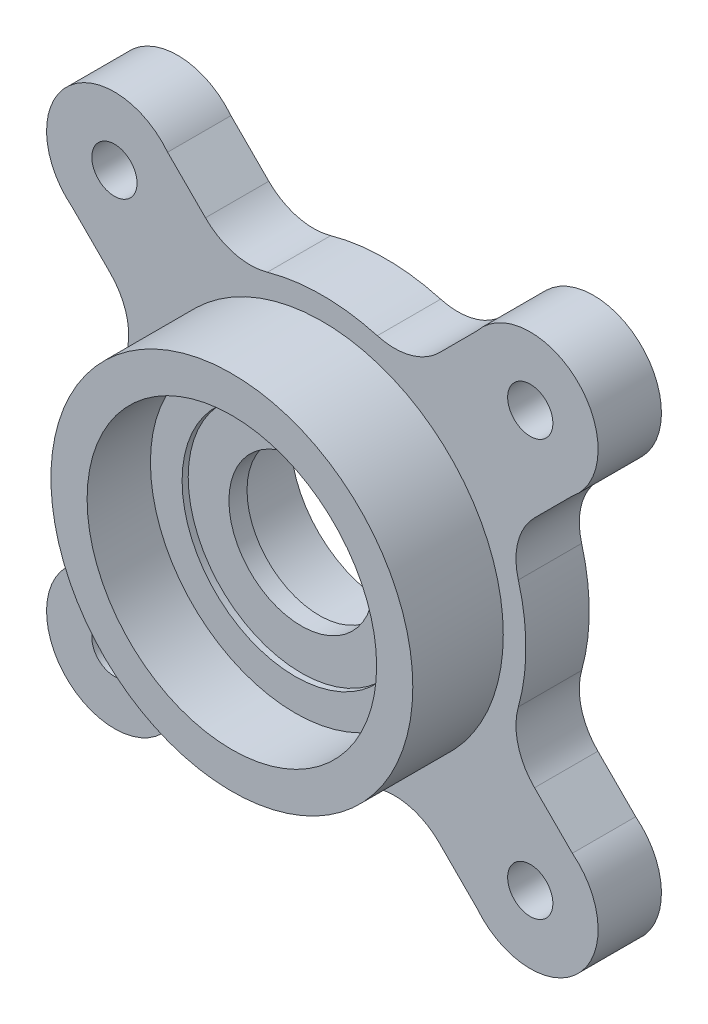
SolidWorks part; units mm, degrees
material "6061 Alloy"
ref_plane "Front Plane" through (0, 0, 0) normal (0, 0, 1) x (1, 0, 0)
ref_plane "Top Plane" through (0, 0, 0) normal (0, 1, 0) x (1, 0, 0)
ref_plane "Right Plane" through (0, 0, 0) normal (1, 0, 0) x (0, 0, -1)
sketch "Sketch1" plane through (0, 0, 0) normal (0, 0, 1) x (1, 0, 0)
  line L0 (17.1012, -27.6369) -> (-27.6369, 17.1012)
  line L1 (-22.981, -22.981) -> (22.981, -22.981) construction
  line L2 (-22.981, -22.981) -> (-22.981, 22.981) construction
  line L3 (-22.981, 22.981) -> (22.981, 22.981) construction
  line L4 (22.981, -22.981) -> (22.981, 22.981) construction
  line L5 (-22.981, -22.981) -> (22.981, 22.981) construction
  line L6 (-22.981, 22.981) -> (22.981, -22.981) construction
  line L7 (17.1012, -27.6369) -> (27.6369, -17.1012)
  line L8 (-27.6369, 17.1012) -> (-17.1012, 27.6369)
  line L9 (27.6369, -17.1012) -> (-17.1012, 27.6369)
  line L10 (17.1012, -27.6369) -> (-17.1012, 27.6369) construction
  line L11 (-27.6369, 17.1012) -> (27.6369, -17.1012) construction
  line L12 (-27.6369, -17.1012) -> (17.1012, 27.6369)
  line L13 (-27.6369, -17.1012) -> (-17.1012, -27.6369)
  line L14 (17.1012, 27.6369) -> (27.6369, 17.1012)
  line L15 (-17.1012, -27.6369) -> (27.6369, 17.1012)
  line L16 (-27.6369, -17.1012) -> (27.6369, 17.1012) construction
  line L17 (17.1012, 27.6369) -> (-17.1012, -27.6369) construction
  circle A0 centre (0, 0) radius 22.5
  circle A1 centre (0, 0) radius 32.5 construction
  circle A2 centre (-22.981, 22.981) radius 7.5
  circle A3 centre (-22.981, -22.981) radius 7.5
  circle A4 centre (22.981, -22.981) radius 7.5
  circle A5 centre (22.981, 22.981) radius 7.5
  point P12 (-22.3691, 22.3691)
  point P13 (22.3691, 22.3691)
  dimension "D1" = 45
  dimension "D2" = 65
  dimension "D3" = 15
extrude ".5 in sheet" add sketch "Sketch1" along normal blind 7 contours A5 A0 A2 A3 A4 | A0 A2 | A0 A5 | A0 A4 | A0 A3 | L8 A2 | A2 L0 A0 L9 | L9 A0 L0 L12 | L12 A0 L9 | L0 A0 L12 | L15 A0 L0 | L0 A0 L9 L15 | L9 A0 L15 | L15 A0 L12 L9 | L0 L15 L9 L12 | L14 A5 | A5 L12 A0 L15 | L7 A4 | A4 L9 A0 L0 | L13 A3 | A3 L15 A0 L12
fillet "Fillet1" radius 7 8 edges at (-9.7446, -20.2804, 3.5) (20.2804, 9.7446, 3.5) (-9.7446, 20.2804, 3.5) (20.2804, -9.7446, 3.5) (-20.2804, 9.7446, 3.5) (9.7446, -20.2804, 3.5) (-20.2804, -9.7446, 3.5) (9.7446, 20.2804, 3.5)
hole_wizard "Ø5.0 Reamed over for shoulder bolt" positions "Sketch6" profile "Sketch5" hole size "Ø5.0" standard "ANSI Metric" end condition through all
sketch "Sketch6" plane through (-11.0554, 12.7771, 7) normal (0, 0, 1) x (1, 0, 0)
  point P0 (-11.9256, 10.2039)
  point P3 (34.0364, 10.2039)
  point P6 (34.0364, -35.7581)
  point P9 (-11.9256, -35.7581)
sketch "Sketch5" plane through (-22.981, 22.981, 7) normal (1, 0, 0) x (0, -1, 0)
  line L0 (0, 0) -> (0, 7)
  line L1 (0, 7) -> (2.5, 7)
  line L2 (2.5, 7) -> (2.5, 0)
  line L5 (2.5, 0) -> (0, 0)
  line L11 (0, -6.35) -> (0, 107.95) construction
  dimension "Thru Hole Dia." = 5
  dimension "Thru Hole Depth" = 7
sketch "Sketch8" plane through (0, 0, 7) normal (0, 0, 1) x (1, 0, 0)
  circle A0 centre (0, 0) radius 20
  dimension "D1" = 40
extrude "Boss-Extrude2" add sketch "Sketch8" along normal blind 10
sketch "Sketch2" plane through (0, 0, 0) normal (0, 0, 1) x (1, 0, 0)
  circle A0 centre (0, 0) radius 8
  dimension "D1" = 16
extrude "Through hole" cut sketch "Sketch2" along normal through all
sketch "Sketch7" plane through (0, 0, 0) normal (0, 0, -1) x (-1, 0, 0)
  circle A0 centre (0, 0) radius 10.5
  dimension "D1" = 21
extrude "Inboard bearing cup" cut sketch "Sketch7" against normal blind 7.325
sketch "Sketch11" plane through (0, 0, 17) normal (0, 0, 1) x (1, 0, 0)
  circle A0 centre (0, 0) radius 12.5
  dimension "D1" = 25
extrude "Cut-Extrude5" cut sketch "Sketch11" against normal offset from surface (7.675 mm away) 2 up to face at (-8, 0, 7.325)
sketch "Sketch12" plane through (0, 0, 17) normal (0, 0, 1) x (1, 0, 0)
  circle A0 centre (0, 0) radius 16
  dimension "D1" = 32
extrude "Cut-Extrude6" cut sketch "Sketch12" against normal blind 7
sketch "Sketch13" plane through (0, 0, 0) normal (0, 0, -1) x (-1, 0, 0)
  line L1 (-12.3744, -12.3744) -> (12.3744, -12.3744) construction
  line L2 (-12.3744, -12.3744) -> (-12.3744, 12.3744) construction
  line L3 (-12.3744, 12.3744) -> (12.3744, 12.3744) construction
  line L4 (12.3744, -12.3744) -> (12.3744, 12.3744) construction
  line L5 (-12.3744, -12.3744) -> (12.3744, 12.3744) construction
  line L6 (-12.3744, 12.3744) -> (12.3744, -12.3744) construction
  circle A0 centre (0, 0) radius 17.5 construction
  circle A1 centre (12.3744, 12.3744) radius 5
  circle A2 centre (-12.3744, 12.3744) radius 5
  circle A3 centre (-12.3744, -12.3744) radius 5
  circle A4 centre (12.3744, -12.3744) radius 5
  dimension "D1" = 35
  dimension "D2" = 10
extrude "Cut-Extrude7" cut sketch "Sketch13" against normal blind 3
